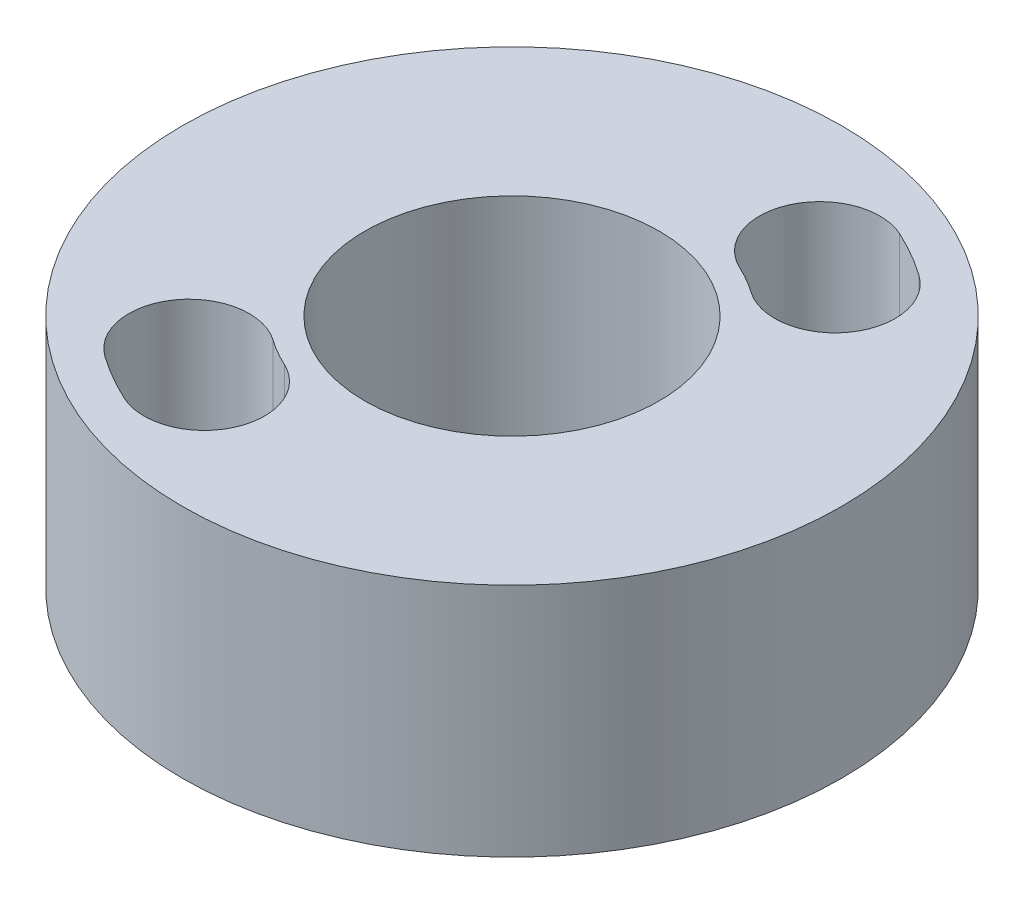
SolidWorks part; units mm, degrees
material "AISI 4130 Steel, normalized at 870C"
ref_plane "Front Plane" through (0, 0, 0) normal (0, 0, 1) x (1, 0, 0)
ref_plane "Top Plane" through (0, 0, 0) normal (0, 1, 0) x (1, 0, 0)
ref_plane "Right Plane" through (0, 0, 0) normal (1, 0, 0) x (0, 0, -1)
sketch "Sketch1" plane through (0, 0, 0) normal (0, 1, 0) x (1, 0, 0)
  circle A0 centre (0, 0) radius 17.78
  circle A1 centre (0, 0) radius 7.9375
  dimension "D1" = 35.56
  dimension "D2" = 15.875
extrude "Boss-Extrude1" add sketch "Sketch1" along normal blind 12.7
sketch "Sketch2" plane through (0, 12.7, 0) normal (0, 1, 0) x (1, 0, 0)
  line L0 (0, 0) -> (8.89, 15.3979) construction
  line L1 (0, 0) -> (0, 17.78) construction
  arc A0 (5.25, 11.3441) -> (7.1992, 10.2187) centre (0, 0) cw construction
  circle A1 centre (0, 0) radius 17.78 construction
  arc A2 (6.615, 14.2935) -> (9.071, 12.8755) centre (0, 0) cw
  arc A3 (3.885, 8.3946) -> (5.3274, 7.5618) centre (0, 0) cw
  arc A4 (6.615, 14.2935) -> (3.885, 8.3946) centre (5.25, 11.3441) ccw
  arc A5 (9.071, 12.8755) -> (5.3274, 7.5618) centre (7.1992, 10.2187) cw
  arc A6 (3.885, 8.3946) -> (5.3274, 7.5618) centre (0, 0) cw construction
  point P4 (6.25, 10.8253)
  point P22 (2, 11.3441)
  dimension "D1" = 12.5
  dimension "D5" = 2
  dimension "D2" = 30
  dimension "D3" = 3.25
  dimension "D4" = 3.25
extrude "Cut-Extrude1" cut sketch "Sketch2" against normal through all
pattern_circular "CirPattern1" count 2 over 360 about axis through (0, 0, 0) along (0, 1, 0) of "Cut-Extrude1"
